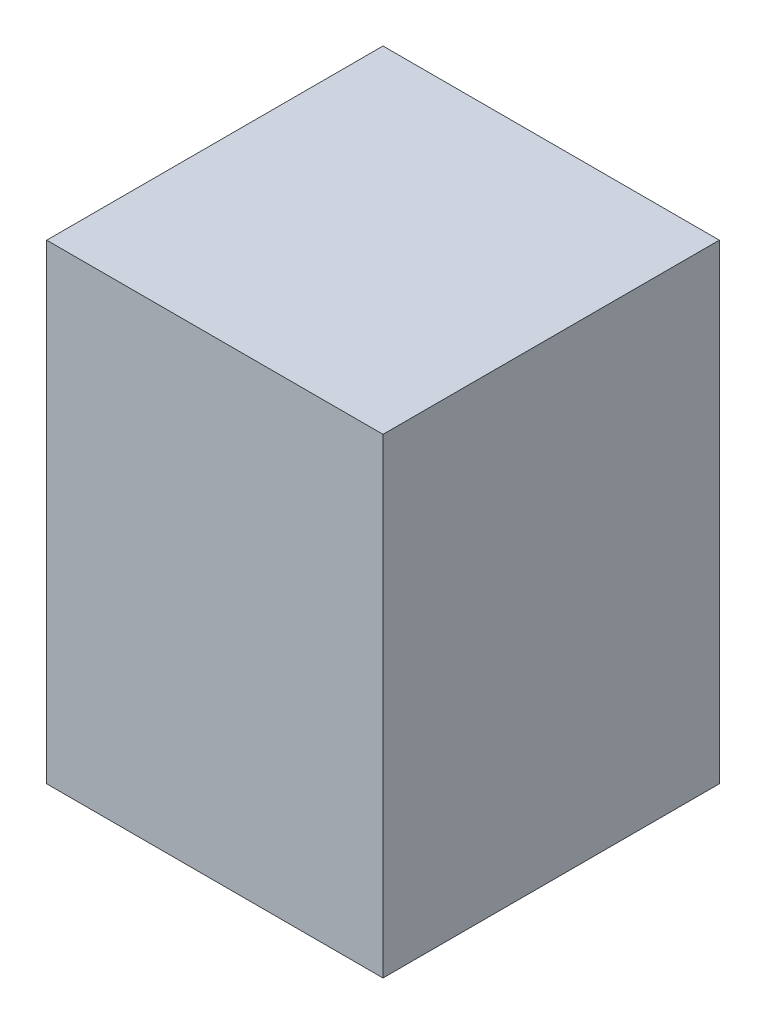
SolidWorks part; units mm, degrees
ref_plane "Front Plane" through (0, 0, 0) normal (0, 0, 1) x (1, 0, 0)
ref_plane "Top Plane" through (0, 0, 0) normal (0, 1, 0) x (1, 0, 0)
ref_plane "Right Plane" through (0, 0, 0) normal (1, 0, 0) x (0, 0, -1)
sketch "Sketch1" plane through (0, 0, 0) normal (0, 1, 0) x (1, 0, 0)
  line L1 (-25, 23.6742) -> (25, 23.6742)
  line L2 (-25, 23.6742) -> (-25, -26.3258)
  line L3 (-25, -26.3258) -> (25, -26.3258)
  line L4 (25, 23.6742) -> (25, -26.3258)
  line L5 (-25, 23.6742) -> (25, -26.3258) construction
  line L6 (-25, -26.3258) -> (25, 23.6742) construction
  point P0 (0, -1.3258)
  dimension "D1" = 50
  dimension "D2" = 50
extrude "Boss-Extrude1" add sketch "Sketch1" against normal blind 70
